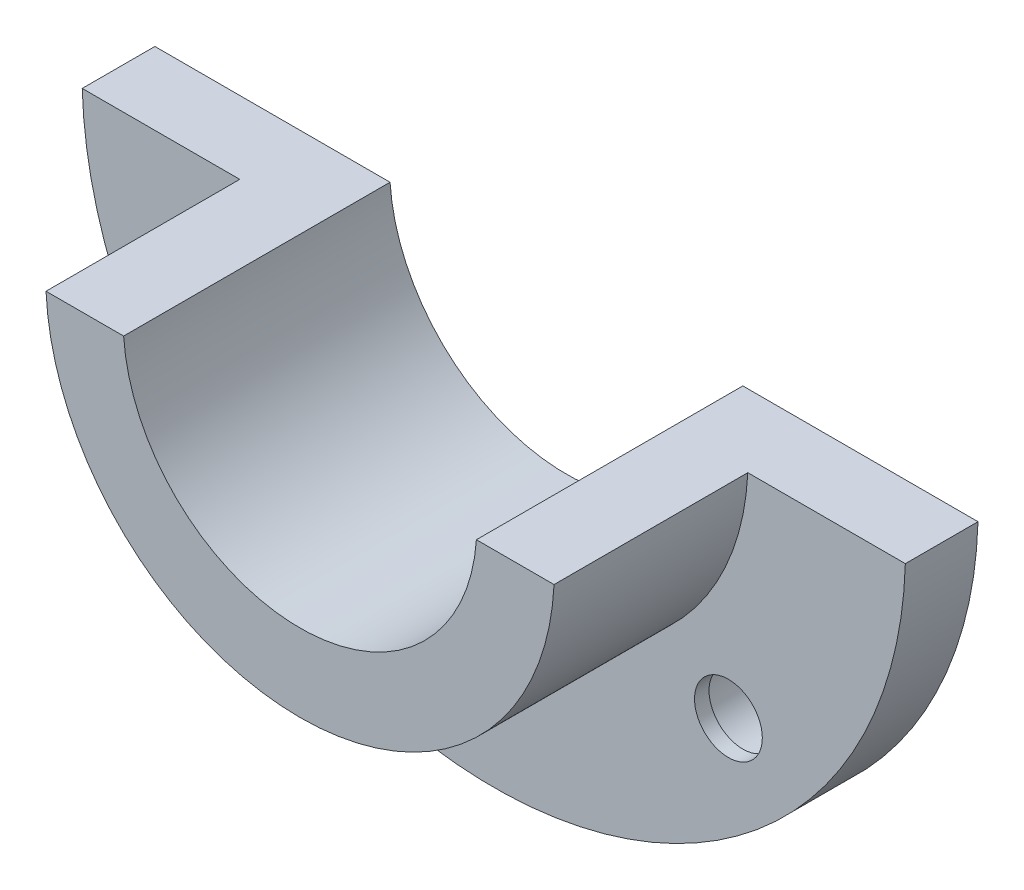
SolidWorks part; units mm, degrees
material "Phosphor bronze 10% D, UNS C52400"
ref_plane "Front Plane" through (0, 0, 0) normal (0, 0, 1) x (1, 0, 0)
ref_plane "Top Plane" through (0, 0, 0) normal (0, 1, 0) x (1, 0, 0)
ref_plane "Right Plane" through (0, 0, 0) normal (1, 0, 0) x (0, 0, -1)
sketch "Sketch1" plane through (0, 0, 0) normal (0, 0, 1) x (1, 0, 0)
  circle A0 centre (0, 0) radius 85
  dimension "D1" = 170
extrude "Boss-Extrude1" add sketch "Sketch1" along normal blind 15
sketch "Sketch2" plane through (0, 0, 15) normal (0, 0, 1) x (1, 0, 0)
  circle A0 centre (0, 0) radius 52.5
  dimension "D1" = 105
extrude "Boss-Extrude2" add sketch "Sketch2" along normal blind 40
sketch "Sketch3" plane through (0, 0, 55) normal (0, 0, 1) x (1, 0, 0)
  circle A0 centre (0, 0) radius 36.5
  dimension "D1" = 73
extrude "Cut-Extrude1" cut sketch "Sketch3" against normal through all both and the other way through all
sketch "Sketch4" plane through (0, 0, 55) normal (0, 0, 1) x (1, 0, 0)
  line L1 (85, 0) -> (-94.4223, 0)
  line L2 (85, 0) -> (85, 89.9516)
  line L3 (85, 89.9516) -> (-94.4223, 89.9516)
  line L4 (-94.4223, 0) -> (-94.4223, 89.9516)
  circle A0 centre (0, 0) radius 85 construction
extrude "Cut-Extrude2" cut sketch "Sketch4" against normal through all both and the other way through all
sketch "Sketch5" plane through (0, 0, 55) normal (0, 0, 1) x (1, 0, 0)
  line L1 (85, 0) -> (-123.7505, 0)
  line L2 (85, 0) -> (85, -2.5)
  line L3 (85, -2.5) -> (-123.7505, -2.5)
  line L4 (-123.7505, 0) -> (-123.7505, -2.5)
  dimension "D1" = 2.5
extrude "Cut-Extrude3" cut sketch "Sketch5" against normal through all both and the other way through all
sketch "Sketch6" plane through (0, 0, 15) normal (0, 0, 1) x (1, 0, 0)
  circle A4 centre (48.4368, -48.4368) radius 7
  circle A6 centre (-48.4368, -48.4368) radius 7
  dimension "D1" = 14
extrude "Cut-Extrude4" cut sketch "Sketch6" against normal through all both and the other way through all
sketch "Sketch8" plane through (0, 0, 0) normal (0, 0, -1) x (-1, 0, 0)
  circle A0 centre (-48.4368, -48.4368) radius 9
  circle A1 centre (48.4368, -48.4368) radius 9
  dimension "D1" = 18
  dimension "D2" = 18
extrude "Cut-Extrude5" cut sketch "Sketch8" against normal blind 12
